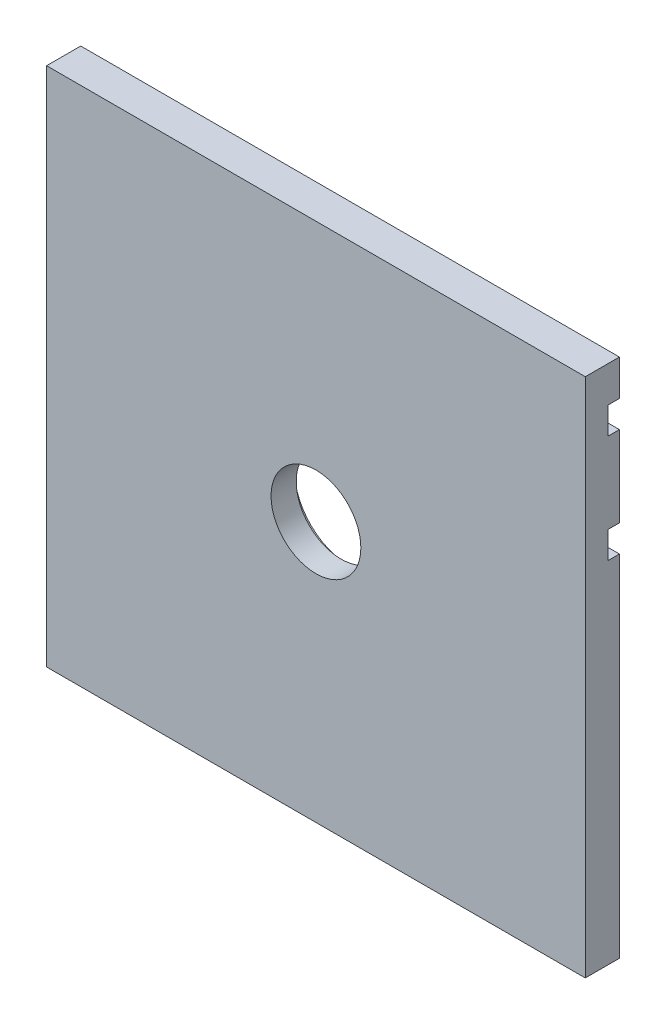
SolidWorks part; units mm, degrees
ref_plane "Plan de face" through (0, 0, 0) normal (0, 0, 1) x (1, 0, 0)
ref_plane "Plan de dessus" through (0, 0, 0) normal (0, 1, 0) x (1, 0, 0)
ref_plane "Plan de droite" through (0, 0, 0) normal (1, 0, 0) x (0, 0, -1)
sketch "Esquisse1" plane through (0, 0, 0) normal (0, 0, 1) x (1, 0, 0)
  line L1 (0, 0) -> (600, 0)
  line L2 (0, 0) -> (0, 580)
  line L3 (0, 580) -> (600, 580)
  line L4 (600, 0) -> (600, 580)
  dimension "D1" = 600
  dimension "D2" = 580
extrude "Boss.-Extru.1" add sketch "Esquisse1" along normal blind 38
sketch "Esquisse2" plane through (0, 0, 38) normal (0, 0, 1) x (1, 0, 0)
  line L0 (300, 0) -> (300, 580) construction
  line L1 (0, 0) -> (600, 0) construction
  line L2 (600, 580) -> (0, 580) construction
  circle A0 centre (300, 290) radius 50
  dimension "D1" = 100
extrude "Enlèv. mat.-Extru.1" cut sketch "Esquisse2" against normal through all both and the other way through all
sketch "Esquisse3" plane through (0, 0, 0) normal (0, 0, 1) x (1, 0, 0)
  circle A0 centre (300, 290) radius 62
  circle A1 centre (300, 290) radius 50 construction
  dimension "D1" = 12
extrude "Enlèv. mat.-Extru.3" cut sketch "Esquisse3" along normal blind 10
sketch "Esquisse4" plane through (0, 0, 0) normal (0, 0, -1) x (-1, 0, 0)
  line L0 (-600, 0) -> (-600, 580) construction
  line L1 (-600, 390) -> (0, 390)
  line L2 (-600, 390) -> (-600, 420)
  line L3 (-600, 420) -> (0, 420)
  line L4 (0, 390) -> (0, 420)
  line L5 (0, 580) -> (0, 0) construction
  line L7 (-600, 540) -> (0, 540)
  line L8 (-600, 540) -> (-600, 510)
  line L9 (-600, 510) -> (0, 510)
  line L10 (0, 540) -> (0, 510)
  circle A1 centre (-300, 290) radius 50 construction
  dimension "D3" = 100
  dimension "D1" = 30
  dimension "D2" = 120
extrude "Enlèv. mat.-Extru.4" cut sketch "Esquisse4" against normal blind 12.8
sketch "Esquisse5" plane through (0, 0, 0) normal (0, 0, -1) x (-1, 0, 0)
  line L0 (-300, 0) -> (-300, 580) construction
  line L1 (0, 0) -> (-600, 0) construction
  line L2 (-600, 580) -> (0, 580) construction
  line L3 (-50, 0) -> (-50, 280)
  line L4 (-520, 0) -> (-550, 0)
  line L5 (-520, 0) -> (-520, 280)
  line L6 (-520, 280) -> (-550, 280)
  line L7 (-550, 0) -> (-550, 280)
  line L8 (-80, 280) -> (-50, 280)
  line L9 (-80, 0) -> (-80, 280)
  line L10 (-80, 0) -> (-50, 0)
  dimension "D1" = 30
  dimension "D2" = 280
  dimension "D3" = 440
extrude "Enlèv. mat.-Extru.5" cut sketch "Esquisse5" against normal blind 12.8
